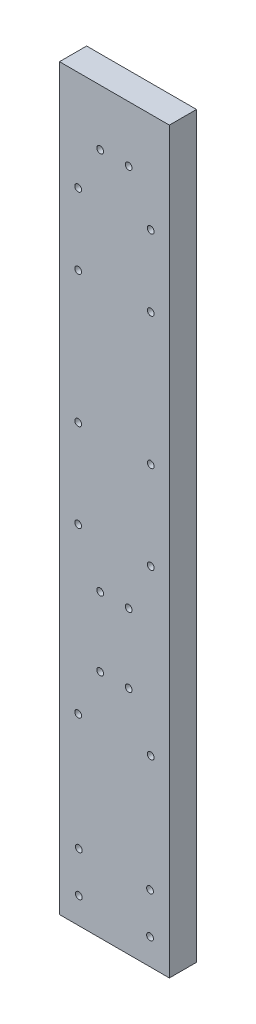
SolidWorks part; units mm, degrees
ref_plane "Front Plane" through (0, 0, 0) normal (0, 0, 1) x (1, 0, 0)
ref_plane "Top Plane" through (0, 0, 0) normal (0, 1, 0) x (1, 0, 0)
ref_plane "Right Plane" through (0, 0, 0) normal (1, 0, 0) x (0, 0, -1)
sketch "Sketch1" plane through (0, 0, 0) normal (0, 0, 1) x (1, 0, 0)
  line L0 (16.2, 0) -> (16.2, 108.91)
  line L1 (16.2, 108.91) -> (0, 108.91)
  line L2 (0, 108.91) -> (0, 0)
  line L3 (0, 0) -> (16.2, 0)
  circle A0 centre (13.45, 51.21) radius 0.5
  circle A1 centre (10.2, 44.21) radius 0.5
  circle A2 centre (10.2, 100.66) radius 0.5
  circle A3 centre (2.75, 94.16) radius 0.5
  circle A4 centre (6, 44.21) radius 0.5
  circle A5 centre (2.75, 27) radius 0.5
  circle A6 centre (2.75, 83.66) radius 0.5
  circle A7 centre (2.75, 51.21) radius 0.5
  circle A28 centre (13.45, 64.21) radius 0.5
  circle A29 centre (6, 34) radius 0.5
  circle A30 centre (13.45, 94.16) radius 0.5
  circle A31 centre (13.45, 83.66) radius 0.5
  circle A32 centre (6, 100.66) radius 0.5
  circle A33 centre (10.2, 34) radius 0.5
  circle A34 centre (2.75, 64.21) radius 0.5
  circle A35 centre (13.45, 27) radius 0.5
  circle A36 centre (2.85, 9.8464) radius 0.5
  circle A37 centre (13.35, 9.8464) radius 0.5
  circle A38 centre (13.35, 3.8464) radius 0.5
  circle A39 centre (2.85, 3.8464) radius 0.5
extrude "Boss-Extrude1" add sketch "Sketch1" along normal blind 4
